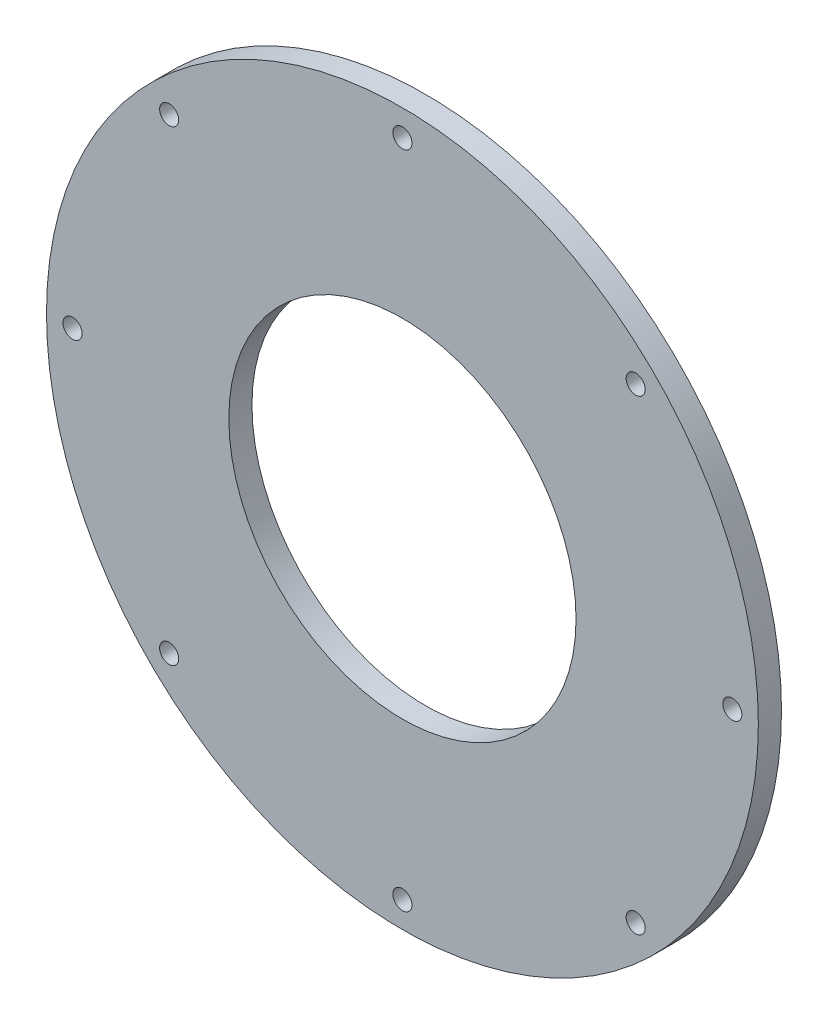
SolidWorks part; units mm, degrees
ref_plane "前视基准面" through (0, 0, 0) normal (0, 0, 1) x (1, 0, 0)
ref_plane "上视基准面" through (0, 0, 0) normal (0, 1, 0) x (1, 0, 0)
ref_plane "右视基准面" through (0, 0, 0) normal (1, 0, 0) x (0, 0, -1)
sketch "草图1" plane through (0, 0, 0) normal (0, 0, 1) x (1, 0, 0)
  line L0 (0, -52.5) -> (0, -61.5) construction
  line L1 (0, 0) -> (36.1973, 0) construction
  line L2 (0, 0) -> (39.2724, -22.6739) construction
  circle A1 centre (0, 0) radius 61.5
  circle A3 centre (0, 0) radius 52.5 construction
  circle A4 centre (0, -57) radius 1.65
  circle A5 centre (0, -57) radius 3.8 construction
  circle A6 centre (-40.3051, -40.3051) radius 1.65
  circle A7 centre (-57, 0) radius 1.65
  circle A8 centre (-40.3051, 40.3051) radius 1.65
  circle A9 centre (0, 0) radius 23.75 construction
  circle A10 centre (0, 0) radius 22.5 construction
  circle A11 centre (0, -23.75) radius 2.6
  circle A12 centre (-20.5681, 11.875) radius 2.6
  circle A13 centre (20.5681, 11.875) radius 2.6
  circle A14 centre (19.4856, -11.25) radius 2.6
  circle A15 centre (-19.4856, -11.25) radius 2.6
  circle A16 centre (0, 22.5) radius 2.6
  circle A17 centre (0, 0) radius 15.5
  circle A18 centre (0, 57) radius 1.65
  circle A19 centre (40.3051, 40.3051) radius 1.65
  circle A20 centre (57, 0) radius 1.65
  circle A21 centre (40.3051, -40.3051) radius 1.65
  dimension "D1" = 47.5
  dimension "D2" = 123
  dimension "D3" = 105
  dimension "D4" = 7.6
  dimension "D6" = 45
  dimension "D7" = 5.2
  dimension "D9" = 5.2
  dimension "D10" = 31
  dimension "D11" = 3.3
  dimension "D8" = 30
  dimension "D5" = 8
extrude "凸台-拉伸1" add sketch "草图1" along normal blind 4
sketch "草图2" plane through (0, 0, 4) normal (0, 0, 1) x (1, 0, 0)
  circle A0 centre (0, 0) radius 30
  dimension "D1" = 60
extrude "切除-拉伸1" cut sketch "草图2" against normal blind 10
